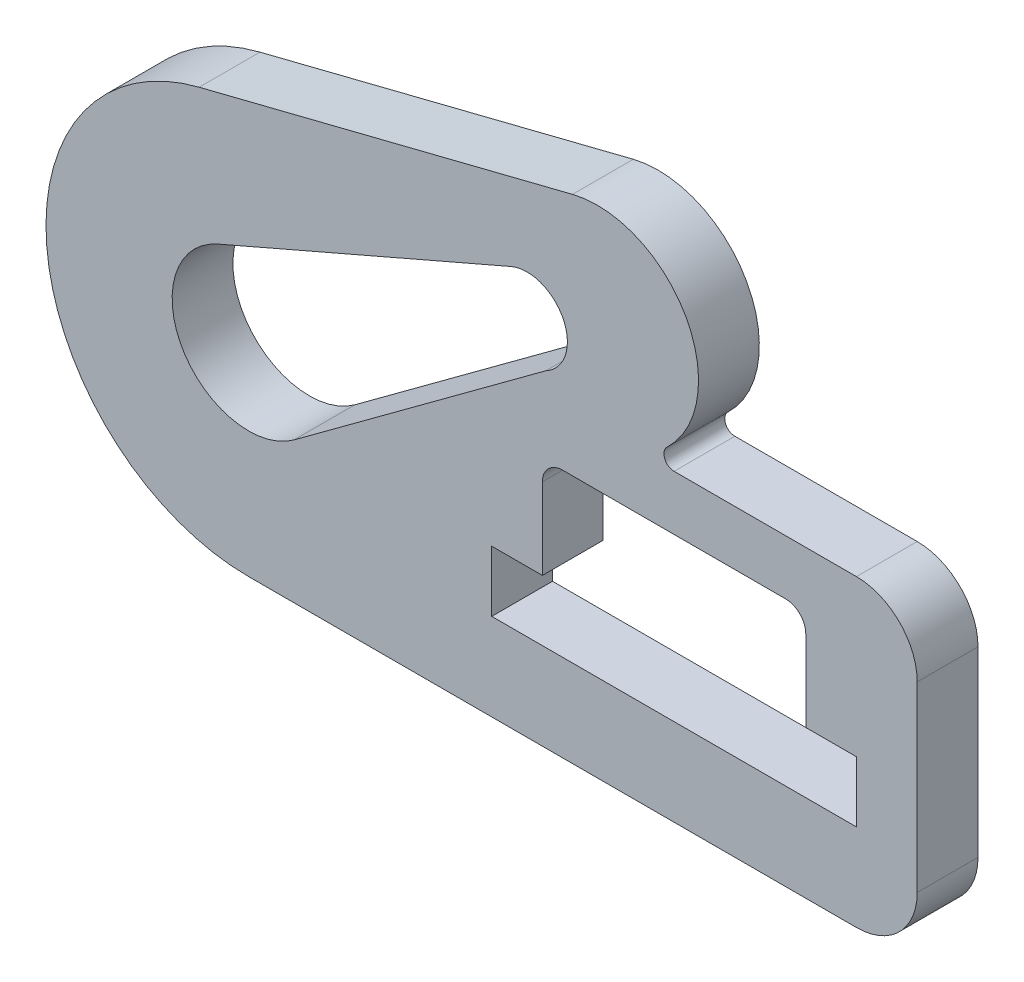
SolidWorks part; units mm, degrees
ref_plane "Front Plane" through (0, 0, 0) normal (0, 0, 1) x (1, 0, 0)
ref_plane "Top Plane" through (0, 0, 0) normal (0, 1, 0) x (1, 0, 0)
ref_plane "Right Plane" through (0, 0, 0) normal (1, 0, 0) x (0, 0, -1)
sketch "Sketch1" plane through (0, 0, 0) normal (0, 0, 1) x (1, 0, 0)
  line L1 (3.8687, 4.667) -> (3.8687, -4.333)
  line L2 (0.8687, -7.333) -> (-29.1313, -7.333)
  line L5 (-8.1313, 7.667) -> (0.8687, 7.667)
  line L6 (-31.5701, 12.365) -> (-13.1438, 16.9988)
  arc A1 (0.8687, 7.667) -> (3.8687, 4.667) centre (0.8687, 4.667) cw
  arc A2 (3.8687, -4.333) -> (0.8687, -7.333) centre (0.8687, -4.333) cw
  arc A7 (-13.1438, 16.9988) -> (-8.4761, 8.5291) centre (-11.9244, 12.1497) cw
  arc A9 (-8.4761, 8.5291) -> (-8.1313, 7.667) centre (-8.1313, 8.167) ccw
  arc A10 (-31.5701, 12.365) -> (-29.1313, -7.333) centre (-29.1313, 2.667) ccw
  dimension "D4" = 3
  dimension "D5" = 3
  dimension "D6" = 33
  dimension "D9" = 0.5
  dimension "D10" = 5
  dimension "D12" = 19
  dimension "D7" = 9
  dimension "D3" = 10
  dimension "D2" = 15
extrude "Boss-Extrude1" add sketch "Sketch1" along normal blind 3
sketch "Sketch2" plane through (0, 0, 3) normal (0, 0, 1) x (1, 0, 0)
  circle A0 centre (-29.1313, 2.667) radius 1.5
  arc A1 (-31.5701, 12.365) -> (-29.1313, -7.333) centre (-29.1313, 2.667) ccw construction
  dimension "D1" = 3
extrude "Cut-Extrude1" cut sketch "Sketch2" against normal blind 3
sketch "Sketch4" plane through (0, 0, 0) normal (0, 0, -1) x (-1, 0, 0)
  line L0 (30.6327, 6.1296) -> (16.1855, 12.3943)
  line L1 (26.8908, -0.3702) -> (14.4504, 8.8069)
  arc A0 (30.6327, 6.1296) -> (26.8908, -0.3702) centre (29.1313, 2.667) cw
  arc A1 (16.1855, 12.3943) -> (14.4504, 8.8069) centre (15.3921, 10.5647) ccw
  arc A3 (29.1313, -7.333) -> (31.5701, 12.365) centre (29.1313, 2.667) ccw construction
  dimension "D1" = 15.8474
  dimension "D2" = 3.985
  dimension "D3" = 7.5
extrude "Cut-Extrude2" cut sketch "Sketch4" against normal blind 3
sketch "Sketch5" plane through (0, 0, 3) normal (0, 0, 1) x (1, 0, 0)
  line L1 (0.8687, -0.033) -> (-17.1313, -0.033)
  line L2 (0.8687, -0.033) -> (0.8687, -3.033)
  line L3 (0.8687, -3.033) -> (-17.1313, -3.033)
  line L4 (-17.1313, -0.033) -> (-17.1313, -3.033)
  line L5 (0.8687, 7.667) -> (-8.1313, 7.667) construction
  line L6 (3.8687, -4.333) -> (3.8687, 4.667) construction
  dimension "D1" = 18
  dimension "D2" = 3
  dimension "D3" = 7.7
  dimension "D4" = 3
extrude "Cut-Extrude3" cut sketch "Sketch5" against normal blind 3
sketch "Sketch7" plane through (0, 0, 3) normal (0, 0, 1) x (1, 0, 0)
  line L0 (-14.6313, -0.033) -> (-14.6313, 3.967)
  line L1 (0.8687, -0.033) -> (-17.1313, -0.033) construction
  line L2 (-13.6313, 4.967) -> (-2.6313, 4.967)
  line L3 (-1.6313, 3.967) -> (-1.6313, -0.033)
  line L4 (-1.6313, -0.033) -> (-14.6313, -0.033)
  line L5 (3.8687, -4.333) -> (3.8687, 4.667) construction
  arc A0 (-14.6313, 3.967) -> (-13.6313, 4.967) centre (-13.6313, 3.967) cw
  arc A1 (-2.6313, 4.967) -> (-1.6313, 3.967) centre (-2.6313, 3.967) cw
  dimension "D1" = 1
  dimension "D2" = 5
  dimension "D3" = 5.5
  dimension "D4" = 13
extrude "Cut-Extrude5" cut sketch "Sketch7" against normal blind 3
